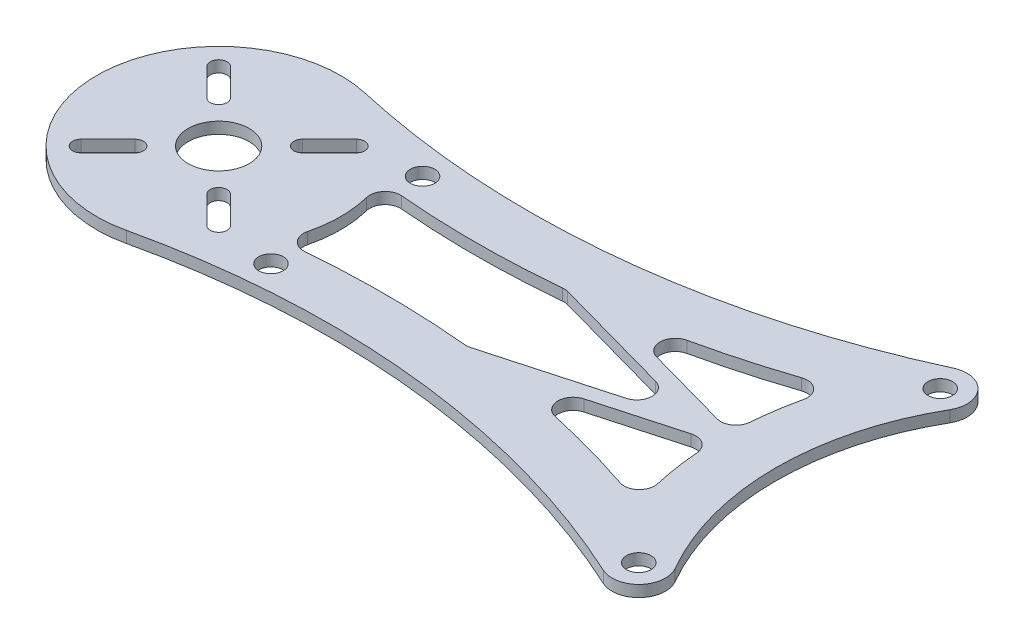
SolidWorks part; units mm, degrees
material "Thornel Mat VMA"
ref_plane "Front Plane" through (0, 0, 0) normal (0, 0, 1) x (1, 0, 0)
ref_plane "Top Plane" through (0, 0, 0) normal (0, 1, 0) x (1, 0, 0)
ref_plane "Right Plane" through (0, 0, 0) normal (1, 0, 0) x (0, 0, -1)
sketch "Sketch1" plane through (0, 0, 0) normal (0, 1, 0) x (1, 0, 0)
  line L0 (0, 0) -> (-43, 0) construction
  line L1 (0, 0) -> (-37.2391, 21.5) construction
  line L2 (0, 0) -> (-37.2391, -21.5) construction
  arc A0 (-37.2391, 21.5) -> (-37.2391, -21.5) centre (0, 0) ccw
  arc A1 (-105.4595, 15.6034) -> (-105.4595, -15.6034) centre (-109, 0) ccw
  arc A2 (-31.1769, 18) -> (-31.1769, -18) centre (0, 0) ccw
  circle A3 centre (-34.208, 19.75) radius 3.5
  circle A4 centre (-34.208, -19.75) radius 3.5
  arc A5 (-105.4595, 15.6034) -> (-35.6743, 22.928) centre (-81.3396, 121.9012) ccw
  arc A6 (-105.4595, -15.6034) -> (-35.6743, -22.928) centre (-81.3396, -121.9012) cw
  dimension "D2" = 32
  dimension "D3" = 86
  dimension "D4" = 7
  dimension "D7" = 109
  dimension "D1" = 109
  dimension "D5" = 30
  dimension "D6" = 30
  dimension "D8" = 0
extrude "Boss-Extrude1" add sketch "Sketch1" along normal mid plane 1.5 contours A1 A6 A4 A0 A3 A5 | A4 A2 A3 A0 | A4 | A3
hole_wizard "Ø2.2 (2.2) Diameter Hole1" positions "Sketch3" profile "Sketch2" hole size "Ø2.2" standard "ANSI Metric"
sketch "Sketch3" plane through (0, 0.75, 0) normal (0, 1, 0) x (1, 0, 0)
  point P39 (-114.4801, 5.4801)
  point P41 (-103.5199, 5.4801)
  point P43 (-103.5199, -5.4801)
  point P45 (-114.4801, -5.4801)
  point P48 (-101.25, 0)
sketch "Sketch2" plane through (-114.4801, 0.75, -5.4801) normal (1, 0, 0) x (0, 0, 1)
  line L0 (0, 0) -> (0, 1.5)
  line L1 (0, 1.5) -> (1.1, 1.5)
  line L2 (1.1, 1.5) -> (1.1, 0)
  line L5 (1.1, 0) -> (0, 0)
  line L11 (0, -6.35) -> (0, 107.95) construction
  dimension "Thru Hole Dia." = 2.2
  dimension "Thru Hole Depth" = 1.5
hole_wizard "Ø3.2 (3.2) Diameter Hole1" positions "Sketch5" profile "Sketch4" hole size "Ø3.2" standard "ANSI Metric"
sketch "Sketch5" plane through (0, 0.75, 0) normal (0, 1, 0) x (1, 0, 0)
  circle A0 centre (-109, 0) radius 16
  circle A1 centre (-92.2167, 9.9283) radius 3.5
  circle A2 centre (-92.2167, -9.9283) radius 3.5
  arc A3 (-35.6743, -22.928) -> (-105.4595, -15.6034) centre (-81.3396, -121.9012) ccw construction
  arc A4 (-105.4595, 15.6034) -> (-35.6743, 22.928) centre (-81.3396, 121.9012) ccw construction
  point P0 (-34.208, 19.75)
  point P3 (-34.208, -19.75)
  point P11 (-92.2167, 9.9283)
  point P13 (-92.2167, -9.9283)
  dimension "D1" = 7
sketch "Sketch4" plane through (-34.208, 0.75, -19.75) normal (1, 0, 0) x (0, 0, 1)
  line L0 (0, 0) -> (0, 10.9614)
  line L1 (0, 10.9614) -> (1.6, 10)
  line L2 (1.6, 10) -> (1.6, 0)
  line L5 (1.6, 0) -> (0, 0)
  line L10 (0, 10.9614) -> (-1.6, 10) construction
  line L11 (0, -6.35) -> (0, 107.95) construction
  dimension "Hole Dia." = 3.2
  dimension "Hole Depth" = 10
  dimension "Drill Angle" = 118
sketch "Sketch6" plane through (0, 0.75, 0) normal (0, 1, 0) x (1, 0, 0)
  line L0 (-43, 0) -> (-67.3057, -6.7532)
  line L1 (-43, 0) -> (-67.3057, 6.7532)
  line L2 (-42.7323, 0.9635) -> (-67.038, 7.7167)
  line L3 (-43.2677, -0.9635) -> (-69.9809, 6.4586)
  line L4 (-43.2677, 0.9635) -> (-69.9809, -6.4586)
  line L5 (-42.7323, -0.9635) -> (-67.038, -7.7167)
  line L6 (-43.2677, -0.9635) -> (-67.5734, 5.7897) construction
  line L7 (-43.2677, 0.9635) -> (-67.5734, -5.7897) construction
  arc A2 (-107.0084, 8.7769) -> (-32.7417, 16.572) centre (-81.3396, 121.9012) ccw
  arc A3 (-94.4446, 6.6438) -> (-40.935, 13.1654) centre (-81.3396, 121.9012) ccw
  arc A5 (-32.7417, -16.572) -> (-107.0084, -8.7769) centre (-81.3396, -121.9012) ccw
  arc A6 (-40.935, -13.1654) -> (-94.4446, -6.6438) centre (-81.3396, -121.9012) ccw
  arc A7 (-94.4446, -6.6438) -> (-94.4446, 6.6438) centre (-109, 0) ccw
  arc A8 (-37.2391, 21.5) -> (-37.2391, -21.5) centre (0, 0) ccw
  arc A9 (-40.935, 13.1654) -> (-40.935, -13.1654) centre (0, 0) ccw
  dimension "D1" = 7
  dimension "D2" = 7
  dimension "D3" = 7
  dimension "D4" = 1
  dimension "D5" = 1
  dimension "D6" = 1
  dimension "D7" = 1
extrude "Cut-Extrude1" cut sketch "Sketch6" against normal through all contours A7 A6 L4 L3 A3 | A9 A3 L2 | A9 L5 A6
fillet "Fillet1" radius 2 11 edges at (-40.935, 0, 13.1654) (-42.9876, 0, -1.0344) (-40.935, 0, -13.1654) (-42.9876, 0, 1.0344) (-64.7797, 0, -7.0893) (-64.7797, 0, 7.0893) (-46.7355, 0, 0) (-69.9809, 0, 6.4586) (-69.9809, 0, -6.4586) (-94.4446, 0, 6.6438) (-94.4446, 0, -6.6438)
sketch "Sketch7" plane through (0, 0.75, 0) normal (0, 1, 0) x (1, 0, 0)
  circle A0 centre (-109, 0) radius 4
  dimension "D1" = 8
extrude "Cut-Extrude2" cut sketch "Sketch7" against normal through all
sketch "Sketch8" plane through (0, 0.75, 0) normal (0, 1, 0) x (1, 0, 0)
  line L0 (-100.7622, 9.7934) -> (-104.2977, 6.2579)
  line L1 (-102.7421, 4.7023) -> (-99.2066, 8.2378)
  line L2 (-103.5199, 5.4801) -> (-103.5199, 50005.4801) construction
  line L3 (-109, 0) -> (-109, 50000) construction
  line L4 (-109, 0) -> (49891, 0) construction
  line L5 (-99.9844, 9.0156) -> (-103.5199, 5.4801) construction
  line L6 (-99.2066, -8.2378) -> (-102.7421, -4.7023)
  line L7 (-104.2977, -6.2579) -> (-100.7622, -9.7934)
  line L8 (-99.9844, -9.0156) -> (-103.5199, -5.4801) construction
  line L9 (-117.2378, -9.7934) -> (-113.7023, -6.2579)
  line L10 (-115.2579, -4.7023) -> (-118.7934, -8.2378)
  line L11 (-118.0156, -9.0156) -> (-114.4801, -5.4801) construction
  line L12 (-118.7934, 8.2378) -> (-115.2579, 4.7023)
  line L13 (-113.7023, 6.2579) -> (-117.2378, 9.7934)
  line L14 (-118.0156, 9.0156) -> (-114.4801, 5.4801) construction
  arc A0 (-99.2066, 8.2378) -> (-100.7622, 9.7934) centre (-99.9844, 9.0156) ccw
  circle A1 centre (-103.5199, 5.4801) radius 1.1 construction
  arc A2 (-102.7421, 4.7023) -> (-104.2977, 6.2579) centre (-103.5199, 5.4801) ccw
  circle A3 centre (-109, 0) radius 4 construction
  circle A4 centre (-109, 0) radius 4
  arc A5 (-100.7622, -9.7934) -> (-99.2066, -8.2378) centre (-99.9844, -9.0156) ccw
  arc A6 (-104.2977, -6.2579) -> (-102.7421, -4.7023) centre (-103.5199, -5.4801) ccw
  arc A7 (-118.7934, -8.2378) -> (-117.2378, -9.7934) centre (-118.0156, -9.0156) ccw
  arc A8 (-115.2579, -4.7023) -> (-113.7023, -6.2579) centre (-114.4801, -5.4801) ccw
  arc A9 (-117.2378, 9.7934) -> (-118.7934, 8.2378) centre (-118.0156, 9.0156) ccw
  arc A10 (-113.7023, 6.2579) -> (-115.2579, 4.7023) centre (-114.4801, 5.4801) ccw
  circle A11 centre (-114.4801, 5.4801) radius 1.1 construction
  point P19 (-119.949, 7.1395)
  point P20 (0, 0)
  point P43 (-109, 0)
  point P45 (-117.5568, -8.5568)
  point P46 (-118.0677, 9.0677)
  point P47 (-117.8676, 8.8676)
  circle M14 centre (-103.5199, 5.4801) radius 1.1
  circle M15 centre (-103.5199, -5.4801) radius 1.1
  dimension "D1" = 45
  dimension "D3" = 5
  dimension "D2" = 4
extrude "Cut-Extrude3" cut sketch "Sketch8" against normal mid plane 10 contours L1 A0 L0 M14 | L7 A5 L6 M15 | L10 A7 L9 A8 | L13 A9 L12 A10
